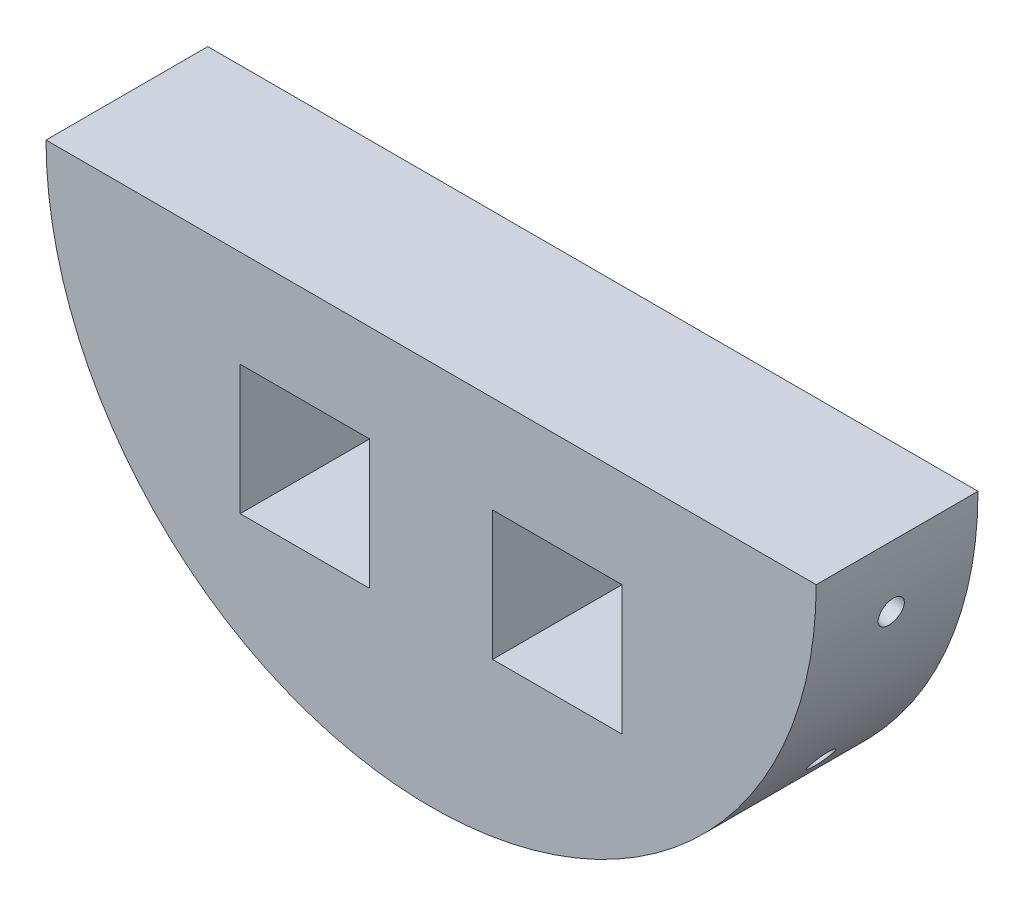
SolidWorks part; units mm, degrees
ref_plane "Front Plane" through (0, 0, 0) normal (0, 0, 1) x (1, 0, 0)
ref_plane "Top Plane" through (0, 0, 0) normal (0, 1, 0) x (1, 0, 0)
ref_plane "Right Plane" through (0, 0, 0) normal (1, 0, 0) x (0, 0, -1)
sketch "Sketch1" plane through (0, 0, 0) normal (0, 0, 1) x (1, 0, 0)
  line L0 (-119, 0) -> (0, 0)
  line L3 (-50, -35) -> (-30, -35)
  line L4 (-50, -35) -> (-50, -15)
  line L5 (-50, -15) -> (-30, -15)
  line L6 (-30, -35) -> (-30, -15)
  line L7 (-89, -35) -> (-69, -35)
  line L8 (-89, -35) -> (-89, -15)
  line L9 (-89, -15) -> (-69, -15)
  line L10 (-69, -35) -> (-69, -15)
  arc A1 (-119, 0) -> (0, 0) centre (-59.5, 0) ccw
  dimension "D1" = 30
  dimension "D7" = 59.5
  dimension "D2" = 15
  dimension "D3" = 30
  dimension "D4" = 20
extrude "Boss-Extrude1" add sketch "Sketch1" along normal blind 25
hole_wizard "Hole1" positions "3DSketch2" profile "Sketch4" legacy
sketch3d "3DSketch2"
  line L2 (0, 0, 25) -> (0, 0, 0) construction
  line L4 (0, 0, 25) -> (0, 0, 0) construction
  line L5 (0, 0, 12.5) -> (-0.9039, -10.3321, 12.5) construction
  line L8 (-59.5, 0, 0) -> (-59.5, 0, 25) construction
  line L9 (0, 0, 0) -> (-119, 0, 0) construction
  line L10 (0, 0, 25) -> (-119, 0, 25) construction
  line L12 (-59.5, 0, 12.5) -> (-0.9039, -10.3321, 12.5) construction
  line L16 (-59.5, 0, 12.5) -> (0, 0, 12.5) construction
  point P0 (-0.9039, -10.3321, 12.5)
  point P16 (-0.9039, -10.3321, 12.5)
  point P23 (-0.9039, -10.3321, 12.5)
  point P25 (-0.9039, -10.3321, 12.5)
  dimension "D1" = 10
sketch "Sketch4" plane through (-0.9039, -10.3321, 12.5) normal (0, 0, 1) x (0.1736, 0.9848, 0)
  line L0 (0, 0) -> (0, 10)
  line L1 (0, 10) -> (2, 10)
  line L2 (2, 10) -> (2, 0)
  line L3 (2, 0) -> (0, 0)
  line L4 (0, 110) -> (0, -10) construction
  dimension "Diameter" = 4
  dimension "Depth" = 10
sketch "Sketch7" plane through (0, 0, 0) normal (0, 0, -1) x (-1, 0, 0)
  line L0 (4.8729, -4.0474) -> (6.783, -14.8803)
  line L1 (4.8729, -4.0474) -> (9.797, -3.1791)
  line L2 (6.783, -14.8803) -> (11.7071, -14.012)
  line L3 (9.797, -3.1791) -> (11.7071, -14.012)
  line L4 (0.9039, -10.3321) -> (59.5, 0) construction
  line L5 (0, 0) -> (119, 0) construction
  arc A0 (0, 0) -> (119, 0) centre (59.5, 0) ccw construction
  point P11 (5.828, -9.4638)
  point P12 (8.0929, -11.0698)
  dimension "D1" = 10
  dimension "D2" = 11
  dimension "D3" = 10
  dimension "D4" = 5
extrude "Cut-Extrude1" cut sketch "Sketch7" against normal blind 18
pattern_circular "CirPattern1" count 7 every 26.667 about axis through (-59.5, 0, 0) along (0, 0, 1) of "Hole1", "Cut-Extrude1"
